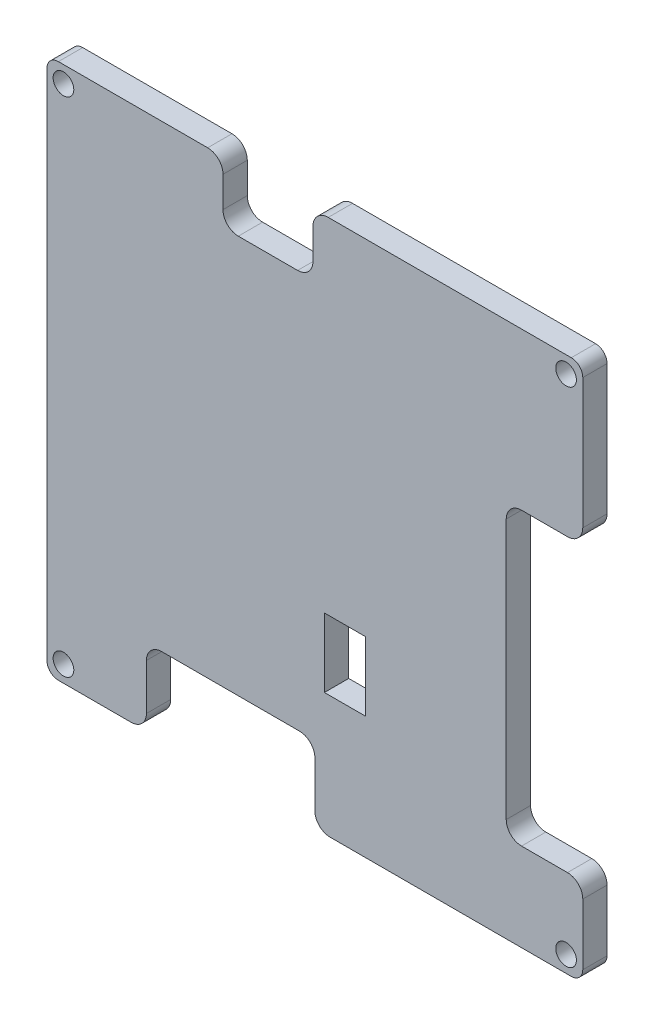
SolidWorks part; units mm, degrees
ref_plane "Front Plane" through (0, 0, 0) normal (0, 0, 1) x (1, 0, 0)
ref_plane "Top Plane" through (0, 0, 0) normal (0, 1, 0) x (1, 0, 0)
ref_plane "Right Plane" through (0, 0, 0) normal (1, 0, 0) x (0, 0, -1)
sketch "Sketch1" plane through (0, 0, 0) normal (0, 0, 1) x (1, 0, 0)
  line L1 (-35, 35) -> (35, 35)
  line L2 (-35, 35) -> (-35, -35)
  line L3 (-35, -35) -> (35, -35)
  line L4 (35, 35) -> (35, -35)
  line L5 (-35, 35) -> (35, -35) construction
  line L6 (-35, -35) -> (35, 35) construction
  circle A0 centre (-32.84, 32.82) radius 1.35
  circle A2 centre (-32.84, -32.84) radius 1.35
  circle A3 centre (32.82, -32.84) radius 1.35
  circle A4 centre (32.82, 32.82) radius 1.35
  point P0 (0, 0)
  dimension "D5" = 2.7
  dimension "D7" = 2.7
  dimension "D9" = 2.7
  dimension "D12" = 2.7
  dimension "D1" = 70
  dimension "D2" = 70
  dimension "D3" = 2.16
  dimension "D4" = 2.16
  dimension "D6" = 65.66
  dimension "D8" = 65.66
  dimension "D10" = 65.66
  dimension "D11" = 65.66
extrude "Boss-Extrude1" add sketch "Sketch1" along normal blind 3.175
fillet "Fillet1" radius 1.5 4 edges at (35, 35, 1.5875) (35, -35, 1.5875) (-35, -35, 1.5875) (-35, 35, 1.5875)
sketch "Sketch2" plane through (0, 0, 0) normal (0, 0, -1) x (-1, 0, 0)
  line L0 (0, 0) -> (35, 0) construction
  line L1 (35, 33.5) -> (35, -33.5) construction
  line L2 (0, 0) -> (0, 35) construction
  line L3 (-33.5, 35) -> (33.5, 35) construction
  line L4 (-25, -23.5) -> (-25, 14.5)
  line L18 (-35, 14.5) -> (-25, 14.5)
  line L19 (-35, -33.5) -> (-35, 33.5) construction
  line L25 (-25, -23.5) -> (-35, -23.5)
  line L26 (-35, 14.5) -> (-35, -23.5)
  line L27 (-33.5, 35) -> (33.5, 35) construction
  dimension "D1" = 20.5
  dimension "D2" = 38
  dimension "D5" = 10
  dimension "D6" = 10
extrude "Cut-Extrude1" cut sketch "Sketch2" against normal through all both and the other way through all
fillet "Fillet2" radius 2 4 edges at (35, -23.5, 1.5875) (35, 14.5, 1.5875) (25, 14.5, 1.5875) (25, -23.5, 1.5875)
sketch "Sketch3" plane through (0, 0, 0) normal (0, 0, -1) x (-1, 0, 0)
  line L0 (33.5, -35) -> (-33.5, -35) construction
  line L1 (22, -35) -> (0, -35)
  line L2 (22, -35) -> (22, -25)
  line L3 (22, -25) -> (0, -25)
  line L4 (0, -35) -> (0, -25)
  line L5 (-33.5, 35) -> (33.5, 35) construction
  line L6 (12, 35) -> (0.25, 35)
  line L7 (12, 35) -> (12, 27)
  line L8 (12, 27) -> (0.25, 27)
  line L9 (0.25, 35) -> (0.25, 27)
  line L10 (35, 33.5) -> (35, -33.5) construction
  line L11 (35, 33.5) -> (35, -33.5) construction
  line L13 (-1.25, -10) -> (-6.6, -10)
  line L14 (-1.25, -10) -> (-1.25, -19)
  line L15 (-1.25, -19) -> (-6.6, -19)
  line L16 (-6.6, -10) -> (-6.6, -19)
  dimension "D1" = 11.75
  dimension "D2" = 23
  dimension "D3" = 8
  dimension "D4" = 13
  dimension "D5" = 22
  dimension "D6" = 10
  dimension "D7" = 5.35
  dimension "D8" = 9
  dimension "D9" = 45
  dimension "D10" = 36.25
extrude "Cut-Extrude2" cut sketch "Sketch3" against normal through all both and the other way through all
fillet "Fillet3" radius 2 8 edges at (0, -35, 1.5875) (-22, -35, 1.5875) (-22, -25, 1.5875) (0, -25, 1.5875) (-12, 27, 1.5875) (-0.25, 27, 1.5875) (-0.25, 35, 1.5875) (-12, 35, 1.5875)
